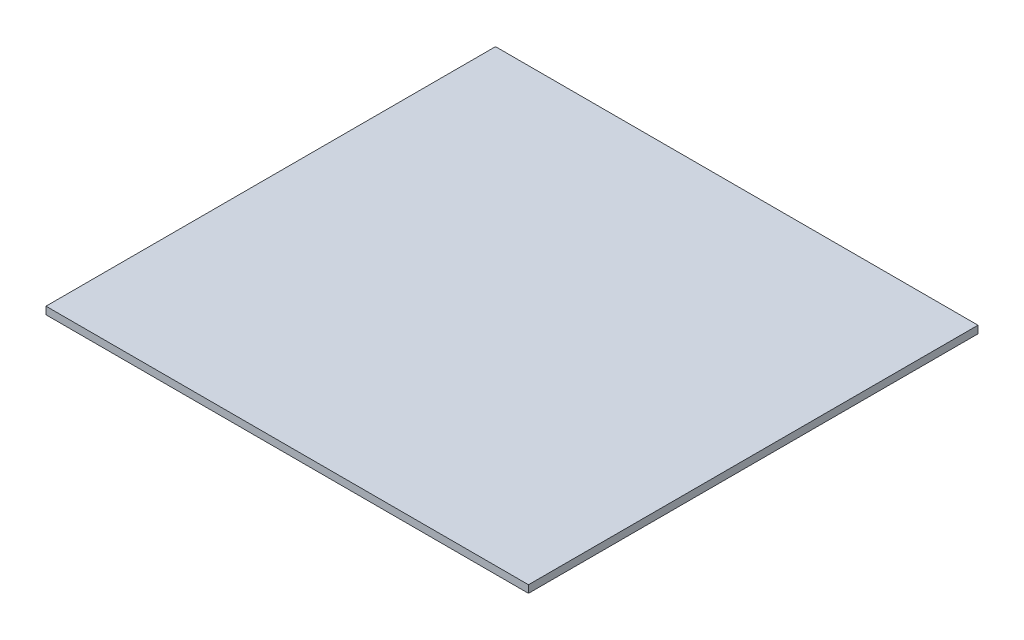
SolidWorks part; units mm, degrees
ref_plane "정면" through (0, 0, 0) normal (0, 0, 1) x (1, 0, 0)
ref_plane "윗면" through (0, 0, 0) normal (0, 1, 0) x (1, 0, 0)
ref_plane "우측면" through (0, 0, 0) normal (1, 0, 0) x (0, 0, -1)
sketch "스케치1" plane through (0, 0, 0) normal (0, 1, 0) x (1, 0, 0)
  line L1 (0, 0) -> (322, 0)
  line L2 (0, 0) -> (0, 300)
  line L3 (0, 300) -> (322, 300)
  line L4 (322, 0) -> (322, 300)
  dimension "D1" = 300
  dimension "D2" = 322
extrude "보스-돌출1" add sketch "스케치1" along normal blind 5
